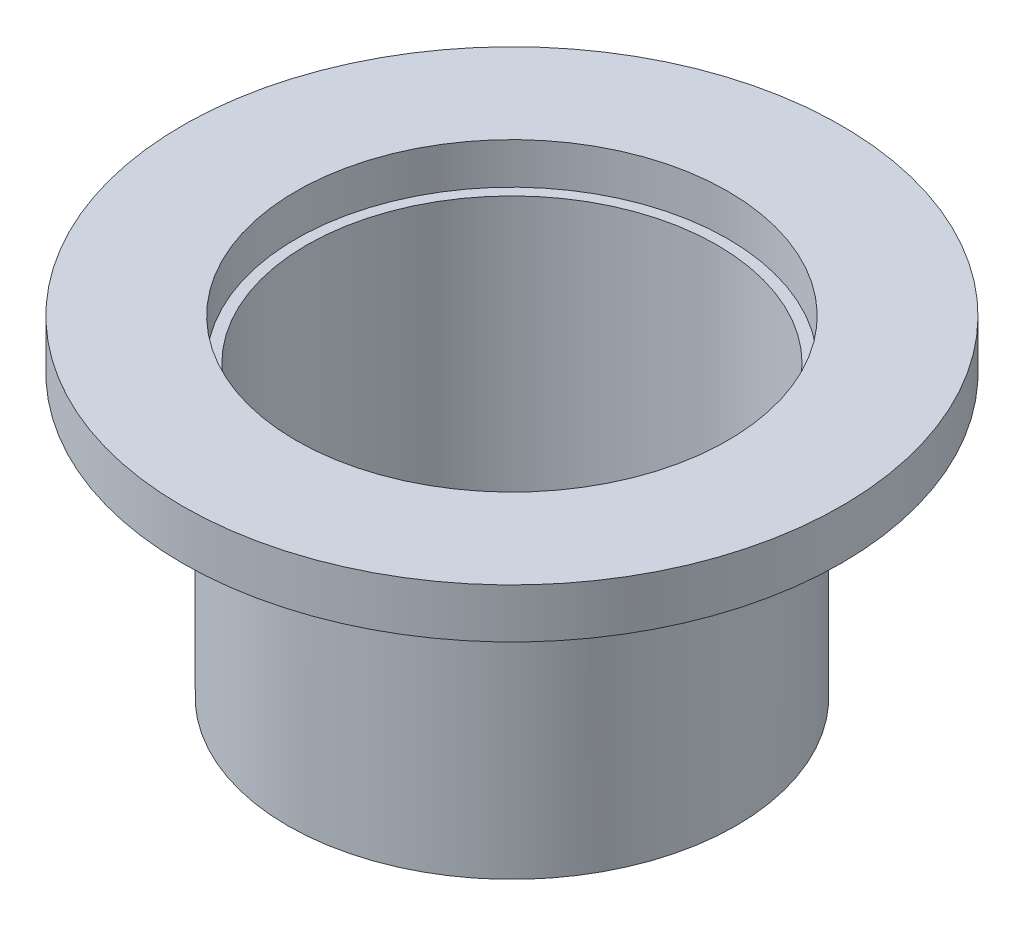
SolidWorks part; units mm, degrees
ref_plane "前视基准面" through (0, 0, 0) normal (0, 0, 1) x (1, 0, 0)
ref_plane "上视基准面" through (0, 0, 0) normal (0, 1, 0) x (1, 0, 0)
ref_plane "右视基准面" through (0, 0, 0) normal (1, 0, 0) x (0, 0, -1)
sketch "草图1" plane through (0, 0, 0) normal (0, 1, 0) x (1, 0, 0)
  circle A0 centre (0, 0) radius 13.6
  circle A1 centre (0, 0) radius 12.45
  dimension "D1" = 27.2
  dimension "D2" = 24.9
extrude "凸台-拉伸1" add sketch "草图1" along normal blind 20
sketch "草图2" plane through (0, 20, 0) normal (0, 1, 0) x (1, 0, 0)
  circle A0 centre (0, 0) radius 20
  dimension "D1" = 40
extrude "凸台-拉伸2" add sketch "草图2" against normal blind 5
sketch "草图3" plane through (0, 20, 0) normal (0, 1, 0) x (1, 0, 0)
  circle A0 centre (0, 0) radius 13.1
  dimension "D1" = 26.2
extrude "切除-拉伸1" cut sketch "草图3" against normal blind 2.5
sketch "草图4" plane through (0, 15, 0) normal (0, -1, 0) x (1, 0, 0)
  circle A0 centre (0, 0) radius 12.45
extrude "切除-拉伸2" cut sketch "草图4" against normal blind 10
sketch "草图5" plane through (0, 0, 0) normal (1, 0, 0) x (0, 0, -1)
  line L0 (20, 20) -> (20, 17) construction
  line L1 (20, 17) -> (13.6, 15)
  line L2 (13.6, 15) -> (20, 15)
  line L3 (20, 15) -> (20, 17)
  dimension "D1" = 3
sketch "草图7" plane through (0, 0, 0) normal (1, 0, 0) x (0, 0, -1)
  line L0 (0, 0) -> (0, 20)
  line L1 (20, 20) -> (-20, 20) construction
revolve "切除-旋转2" cut sketch "草图5" angle 360 about L0
